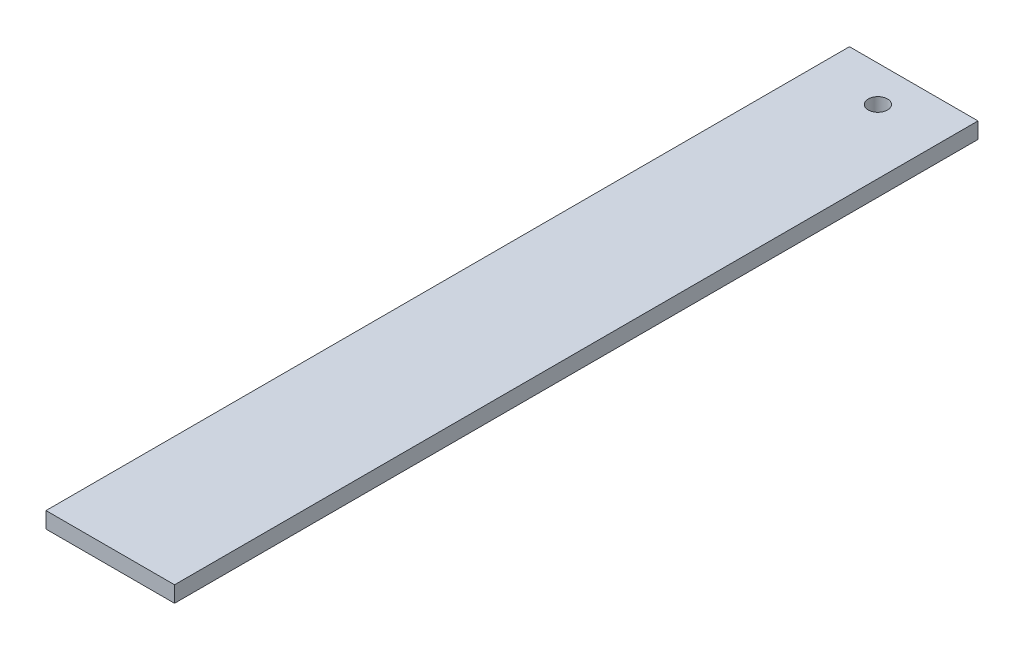
SolidWorks part; units mm, degrees
ref_plane "Front Plane" through (0, 0, 0) normal (0, 0, 1) x (1, 0, 0)
ref_plane "Top Plane" through (0, 0, 0) normal (0, 1, 0) x (1, 0, 0)
ref_plane "Right Plane" through (0, 0, 0) normal (1, 0, 0) x (0, 0, -1)
sketch "Sketch1" plane through (0, 0, 0) normal (0, 1, 0) x (1, 0, 0)
  line L0 (20, 0) -> (20, -71.9021) construction
  line L1 (0, 0) -> (40, 0)
  line L2 (0, 0) -> (0, -250)
  line L3 (0, -250) -> (40, -250)
  line L4 (40, 0) -> (40, -250)
  circle A0 centre (20, -11.1449) radius 2.9951
  dimension "D1" = 40
  dimension "D2" = 250
extrude "Boss-Extrude1" add sketch "Sketch1" along normal blind 5
